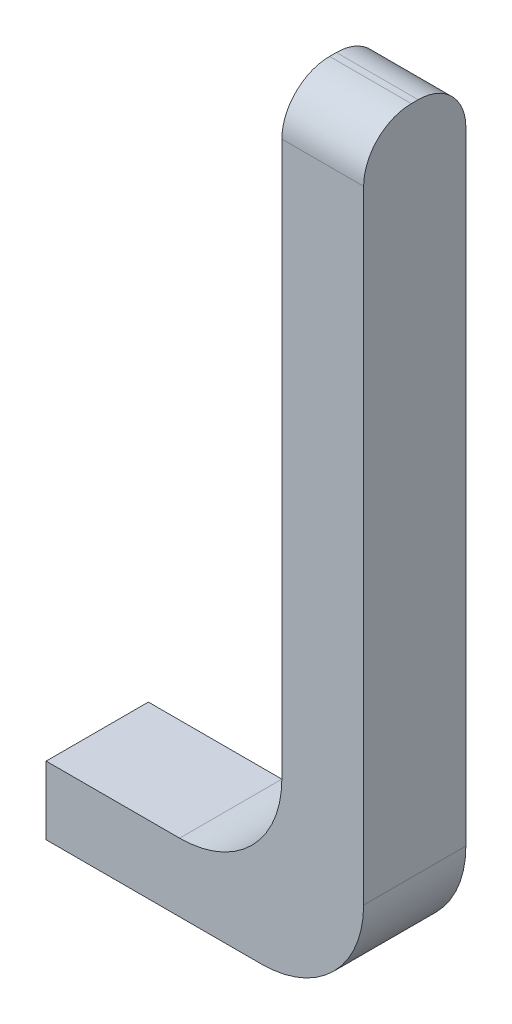
SolidWorks part; units mm, degrees
ref_plane "Front Plane" through (0, 0, 0) normal (0, 0, 1) x (1, 0, 0)
ref_plane "Top Plane" through (0, 0, 0) normal (0, 1, 0) x (1, 0, 0)
ref_plane "Right Plane" through (0, 0, 0) normal (1, 0, 0) x (0, 0, -1)
sketch "Sketch1" plane through (0, 0, 0) normal (0, 0, 1) x (1, 0, 0)
  line L0 (81.8142, 422.2536) -> (101.3962, 422.2536)
  line L1 (116.3962, 437.2536) -> (116.3962, 525.5762)
  line L2 (116.3962, 525.5762) -> (128.3962, 525.5762)
  line L3 (128.3962, 525.5762) -> (128.3962, 427.2536)
  line L4 (113.3962, 412.2536) -> (81.8142, 412.2536)
  line L6 (107.4, 510.5762) -> (124.9621, 510.5762) construction
  line L7 (81.8142, 422.2536) -> (81.8142, 412.2536)
  arc A0 (128.3962, 427.2536) -> (113.3962, 412.2536) centre (113.3962, 427.2536) cw
  arc A1 (101.3962, 422.2536) -> (116.3962, 437.2536) centre (101.3962, 437.2536) ccw
  dimension "D4" = 15
  dimension "D1" = 12
  dimension "D3" = 15
extrude "Boss-Extrude1" add sketch "Sketch1" against normal up to surface (15 mm away)
fillet "Fillet1" radius 7 2 edges at (122.3962, 525.5762, -15) (122.3962, 525.5762, 0)
